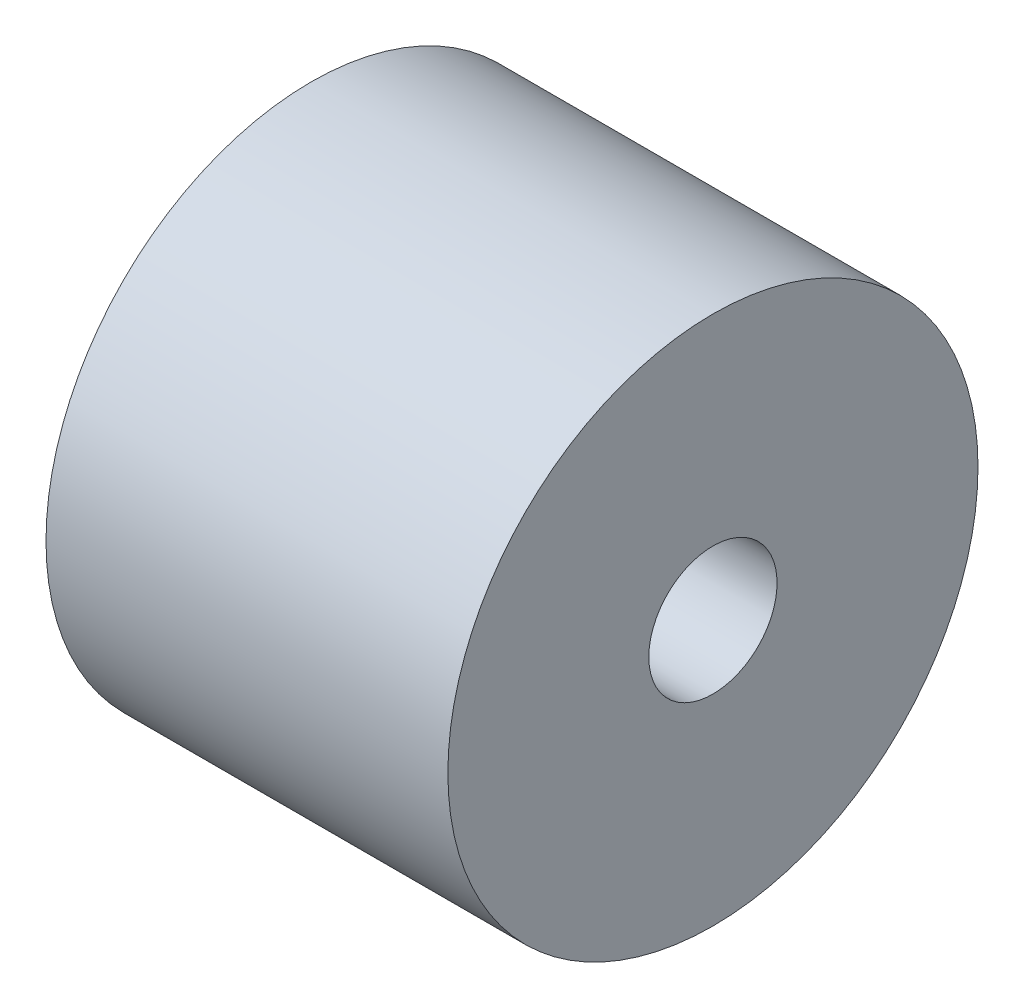
SolidWorks part; units mm, degrees
ref_plane "Plan de face" through (0, 0, 0) normal (0, 0, 1) x (1, 0, 0)
ref_plane "Plan de dessus" through (0, 0, 0) normal (0, 1, 0) x (1, 0, 0)
ref_plane "Plan de droite" through (0, 0, 0) normal (1, 0, 0) x (0, 0, -1)
sketch "Esquisse1" plane through (0, 0, 0) normal (1, 0, 0) x (0, 0, -1)
  circle A0 centre (0, 0) radius 6.2
  dimension "D1" = 12.4
extrude "Boss.-Extru.2" add sketch "Esquisse1" along normal blind 9.4
sketch "Esquisse8" plane through (0, 0, 0) normal (-1, 0, 0) x (0, 0, 1)
  circle A0 centre (0, 0) radius 1.5
  dimension "D1" = 3
extrude "Enlèv. mat.-Extru.1" cut sketch "Esquisse8" against normal through all
